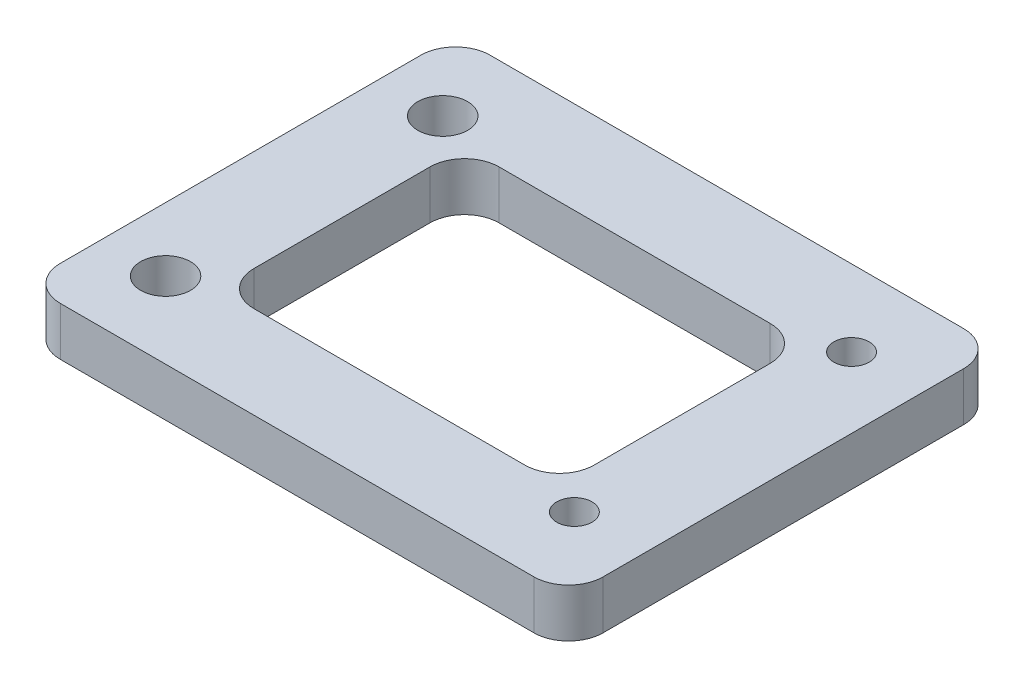
SolidWorks part; units mm, degrees
ref_plane "Front Plane" through (0, 0, 0) normal (0, 0, 1) x (1, 0, 0)
ref_plane "Top Plane" through (0, 0, 0) normal (0, 1, 0) x (1, 0, 0)
ref_plane "Right Plane" through (0, 0, 0) normal (1, 0, 0) x (0, 0, -1)
sketch "Sketch1" plane through (0, 0, 0) normal (0, 1, 0) x (1, 0, 0)
  line L10 (-24.5579, -17.7049) -> (24.5579, -17.7049)
  line L11 (-24.5579, -17.7049) -> (-24.5579, 17.7049)
  line L16 (-24.5579, 17.7049) -> (24.5579, 17.7049)
  line L17 (24.5579, -17.7049) -> (24.5579, 17.7049)
  line L18 (-24.5579, -17.7049) -> (24.5579, 17.7049) construction
  line L19 (-24.5579, 17.7049) -> (24.5579, -17.7049) construction
  line L20 (-39.1771, -31.0193) -> (39.1771, -31.0193)
  line L21 (-39.1771, -31.0193) -> (-39.1771, 31.0193)
  line L22 (-39.1771, 31.0193) -> (39.1771, 31.0193)
  line L23 (39.1771, -31.0193) -> (39.1771, 31.0193)
  line L24 (-39.1771, -31.0193) -> (39.1771, 31.0193) construction
  line L25 (-39.1771, 31.0193) -> (39.1771, -31.0193) construction
  circle A0 centre (29, 20) radius 2.55
  circle A1 centre (29, -20) radius 2.55
  circle A2 centre (-30, -20) radius 3.6
  circle A3 centre (-30, 20) radius 3.6
  point P0 (0, 0)
  point P13 (0, 0)
  point P18 (-33.4281, 14.206)
  point P19 (25.5719, -25.794)
  point P20 (-25.5719, 25.794)
  point P21 (33.4281, -14.206)
  point P22 (-25.5719, -25.794)
  point P23 (33.4281, 14.206)
  point P25 (25.5719, 25.794)
  dimension "D3" = 20
  dimension "D4" = 7.2
  dimension "D5" = 20
  dimension "D6" = 5.1
  dimension "D1" = 29
  dimension "D2" = 30
  dimension "D7" = 15
  dimension "D8" = 5
  dimension "D9" = 24.5579
  dimension "D10" = 39.1771
extrude "Boss-Extrude1" add sketch "Sketch1" along normal blind 7
fillet "Fillet2" radius 5 8 edges at (-39.1771, 3.5, 31.0193) (-24.5579, 3.5, 17.7049) (39.1771, 3.5, 31.0193) (24.5579, 3.5, 17.7049) (24.5579, 3.5, -17.7049) (39.1771, 3.5, -31.0193) (-39.1771, 3.5, -31.0193) (-24.5579, 3.5, -17.7049)
